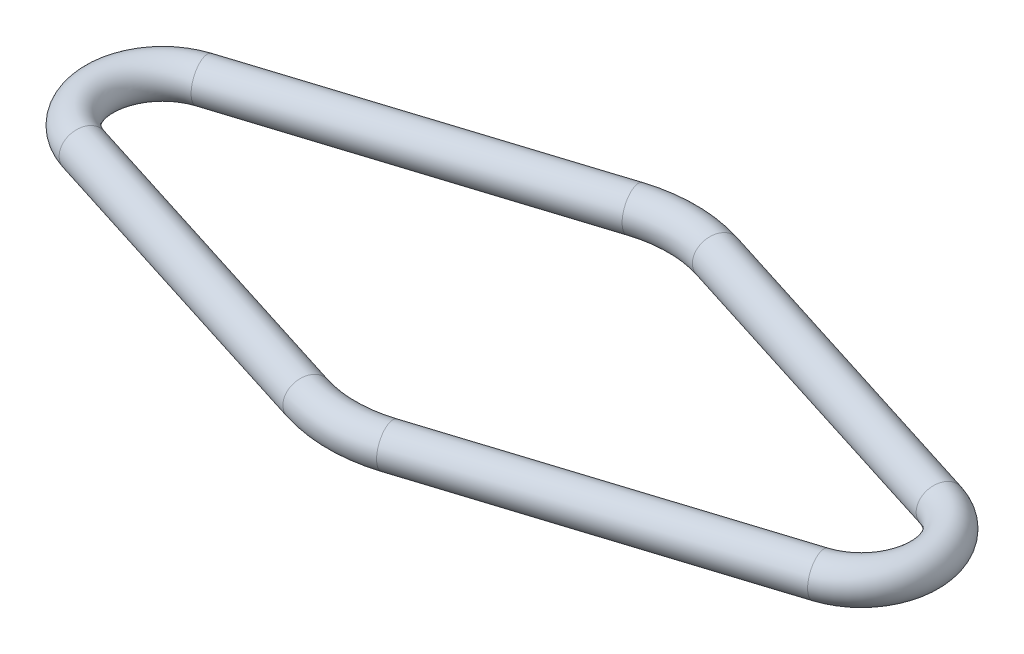
SolidWorks part; units mm, degrees
material "Silicon Rubber"
ref_plane "Front Plane" through (0, 0, 0) normal (0, 0, 1) x (1, 0, 0)
ref_plane "Top Plane" through (0, 0, 0) normal (0, 1, 0) x (1, 0, 0)
ref_plane "Right Plane" through (0, 0, 0) normal (1, 0, 0) x (0, 0, -1)
sketch "FlowPath" plane through (0, 0, 0) normal (0, 1, 0) x (1, 0, 0)
  line L0 (-14.4, 0) -> (14.4, 0) construction
  line L1 (0, -1.4111) -> (0, 1.4111) construction
  line L20 (-15.1846, -2.4788) -> (-1.6898, -6.75)
  line L21 (1.6898, -6.75) -> (15.1846, -2.4788)
  line L22 (15.1846, 2.4788) -> (1.6898, 6.75)
  line L23 (-1.6898, 6.75) -> (-15.1846, 2.4788)
  arc A20 (-1.6898, -6.75) -> (1.6898, -6.75) centre (0, -1.4111) ccw
  arc A21 (15.1846, -2.4788) -> (15.1846, 2.4788) centre (14.4, 0) ccw
  arc A22 (1.6898, 6.75) -> (-1.6898, 6.75) centre (0, 1.4111) ccw
  arc A23 (-15.1846, 2.4788) -> (-15.1846, -2.4788) centre (-14.4, 0) ccw
  point P0 (0, 0)
  point P1 (0, 0)
  point P2 (0, 0)
  dimension "D1" = 2.6
  dimension "D2" = 5.6
  dimension "D3" = 28.8
  dimension "D4" = 2.8222
ref_plane "O-RingProfileStartPlane" through (-1.6898, 0, 6.75) normal (0.9534, 0, 0.3018) x (0.3018, 0, -0.9534)
sketch "Dia" plane through (-1.6898, 0, 6.75) normal (0.9534, 0, 0.3018) x (0.3018, 0, -0.9534)
  circle A0 centre (0, 0) radius 0.8
  dimension "Dim" = 1.6
sweep "O-Ring" add profiles "Dia" path "FlowPath"
